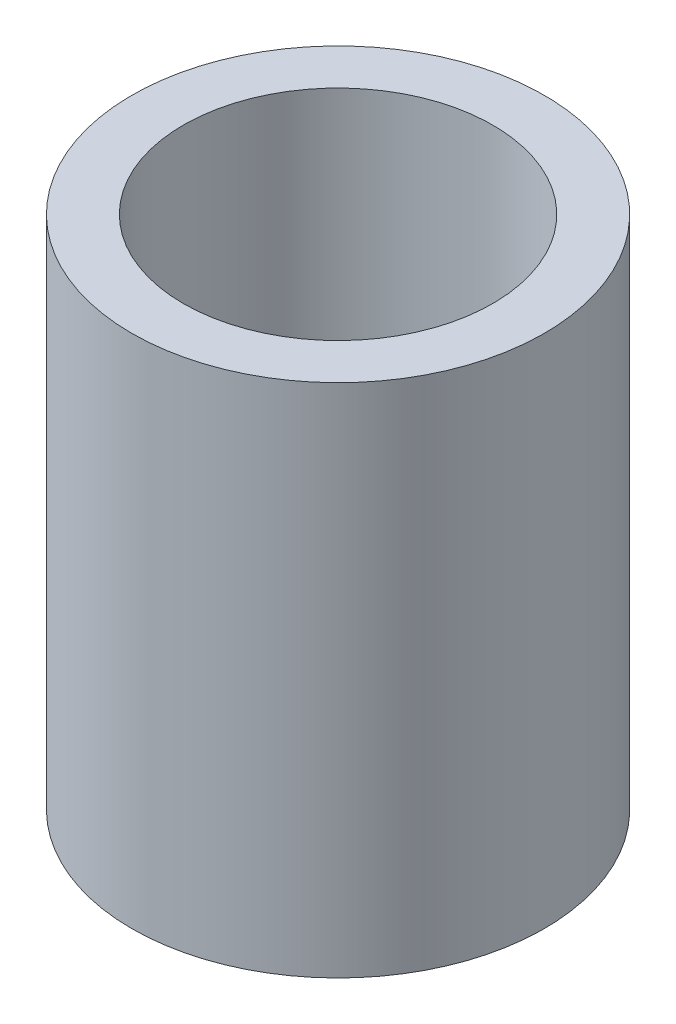
SolidWorks part; units mm, degrees
ref_plane "Front Plane" through (0, 0, 0) normal (0, 0, 1) x (1, 0, 0)
ref_plane "Top Plane" through (0, 0, 0) normal (0, 1, 0) x (1, 0, 0)
ref_plane "Right Plane" through (0, 0, 0) normal (1, 0, 0) x (0, 0, -1)
sketch "Sketch2" plane through (0, 0, 0) normal (0, 1, 0) x (1, 0, 0)
  circle A0 centre (0, 0) radius 10.16
extrude "Boss-Extrude1" add sketch "Sketch2" along normal blind 25.4
sketch "Sketch3" plane through (0, 25.4, 0) normal (0, 1, 0) x (1, 0, 0)
  circle A0 centre (0, 0) radius 7.62
extrude "Cut-Extrude1" cut sketch "Sketch3" against normal blind 20.32
sketch "Sketch4" plane through (0, 0, 0) normal (0, -1, 0) x (1, 0, 0)
  circle A0 centre (0, 0) radius 0.889
extrude "Cut-Extrude2" cut sketch "Sketch4" against normal blind 3.048
chamfer "Chamfer1" distance 0.381 angle 45 1 edges at (0, 0, -0.889)
chamfer "Chamfer2" distance 0.2159 angle 75 1 edges at (0, 3.048, -0.889)
equation "\".8n\"=1"
